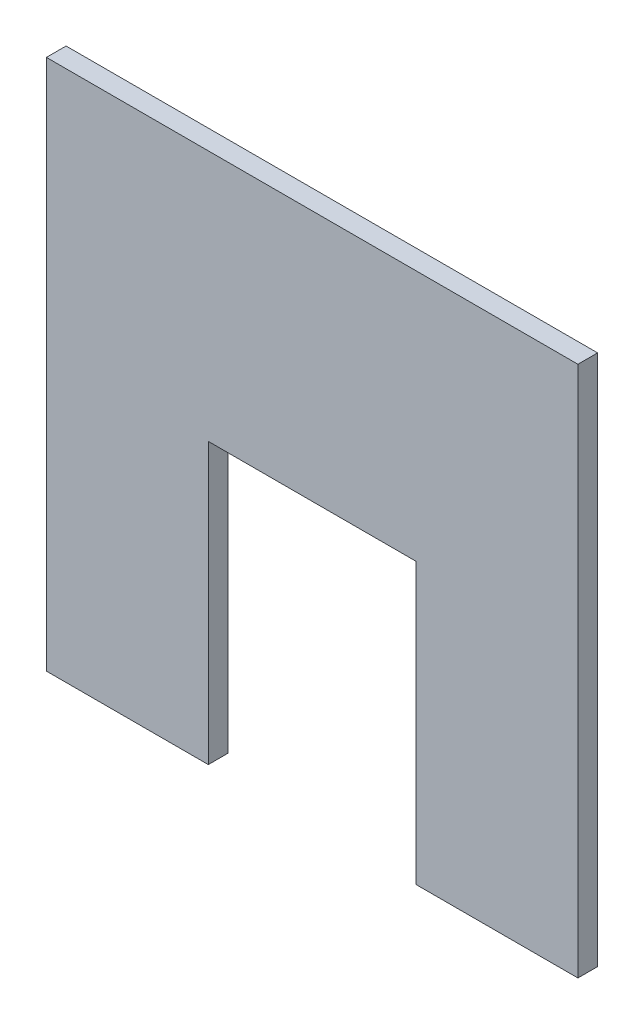
SolidWorks part; units mm, degrees
ref_plane "Front Plane" through (0, 0, 0) normal (0, 0, 1) x (1, 0, 0)
ref_plane "Top Plane" through (0, 0, 0) normal (0, 1, 0) x (1, 0, 0)
ref_plane "Right Plane" through (0, 0, 0) normal (1, 0, 0) x (0, 0, -1)
sketch "Sketch1" plane through (0, 0, 0) normal (0, 0, 1) x (1, 0, 0)
  line L1 (-44.2377, 20.1068) -> (24.3423, 20.1068)
  line L2 (-44.2377, 20.1068) -> (-44.2377, -48.4732)
  line L3 (-44.2377, -48.4732) -> (24.3423, -48.4732)
  line L4 (24.3423, 20.1068) -> (24.3423, -48.4732)
extrude "Boss-Extrude2" add sketch "Sketch1" along normal blind 2.54
sketch "Sketch3" plane through (0, 0, 2.54) normal (0, 0, 1) x (1, 0, 0)
  line L0 (-44.2377, -48.4732) -> (24.3423, -48.4732) construction
  line L1 (-23.3464, -84.5903) -> (3.4509, -84.5903)
  line L2 (-23.3464, -84.5903) -> (-23.3464, -12.3561)
  line L3 (-23.3464, -12.3561) -> (3.4509, -12.3561)
  line L4 (3.4509, -84.5903) -> (3.4509, -12.3561)
  line L5 (-23.3464, -84.5903) -> (3.4509, -12.3561) construction
  line L6 (-23.3464, -12.3561) -> (3.4509, -84.5903) construction
  point P0 (-9.9477, -48.4732)
extrude "Cut-Extrude2" cut sketch "Sketch3" against normal blind 36.576
